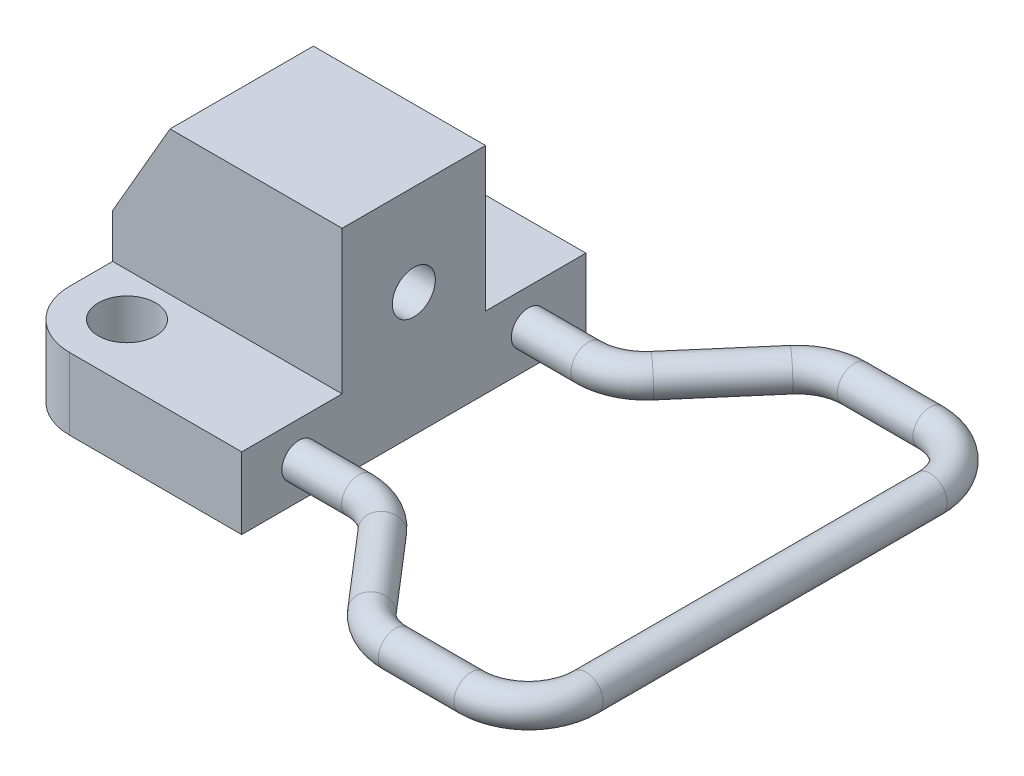
SolidWorks part; units mm, degrees
ref_plane "前视基准面" through (0, 0, 0) normal (0, 0, 1) x (1, 0, 0)
ref_plane "上视基准面" through (0, 0, 0) normal (0, 1, 0) x (1, 0, 0)
ref_plane "右视基准面" through (0, 0, 0) normal (1, 0, 0) x (0, 0, -1)
other "Configuration Table"
sketch "草图15" plane through (0, 0, 0) normal (1, 0, 0) x (0, 0, -1)
  line L0 (-60, 0) -> (-25, 0)
  line L1 (-25, 0) -> (-25, 50)
  line L2 (-25, 50) -> (25, 50)
  line L3 (25, 50) -> (25, 0)
  line L4 (25, 0) -> (60, 0)
  line L5 (60, 0) -> (60, -25)
  line L6 (60, -25) -> (-60, -25)
  line L7 (-60, -25) -> (-60, 0)
  line L8 (0, 58.9623) -> (0, -46.6981) construction
  dimension "D1" = 25
  dimension "D2" = 50
  dimension "D3" = 120
  dimension "D4" = 50
extrude "凸台-拉伸3" add sketch "草图15" along normal mid plane 80
fillet "圆角1" radius 20 2 edges at (-40, -12.5, -60) (-40, -12.5, 60)
sketch "草图17" plane through (0, 0, 0) normal (0, 1, 0) x (1, 0, 0)
  circle A0 centre (-20, 40) radius 10
  arc A1 (-20, 60) -> (-40, 40) centre (-20, 40) ccw construction
  point P2 (-20.8857, 43.4487)
  dimension "D2" = 20
  dimension "D1" = 0
extrude "切除-拉伸2" cut sketch "草图17" against normal through all
mirror "镜向1" about plane through (0, 0, 0) normal (0, 0, 1) of "切除-拉伸2"
chamfer "倒角1" distance 20 angle 60 1 edges at (-40, 50, 0)
sketch "草图19" plane through (0, 0, 0) normal (0, 0, 1) x (1, 0, 0)
  line L0 (-30, 32.6795) -> (-11.9086, 22.2344)
  line L1 (-20, 50) -> (-40, 15.359) construction
  line L2 (3.0914, 18.2152) -> (40, 18.2152)
  line L3 (40, 50) -> (40, 0) construction
  line L4 (40, 50) -> (-20, 50) construction
  arc A0 (-11.9086, 22.2344) -> (3.0914, 18.2152) centre (3.0914, 48.2152) ccw
  point P11 (-30, 32.6795)
  dimension "D1" = 30
  dimension "D2" = 31.7848
sweep "切除-扫描2" cut path "草图19" circular profile diameter 15 parameters "D3"=15
ref_plane "基准面2" through (0, -12.5, 0) normal (0, 1, 0) x (1, 0, 0)
sketch "草图26" plane through (0, -12.5, 0) normal (0, 1, 0) x (1, 0, 0)
  line L0 (0, 0) -> (142.0119, 0) construction
  line L1 (40, 40) -> (60.8279, 40)
  line L2 (40, 60) -> (40, 25) construction
  line L3 (75.9844, 46.9508) -> (98.4541, 73.0492)
  line L4 (113.6106, 80) -> (140, 80)
  line L5 (160, 60) -> (160, -60)
  line L6 (40, 25) -> (40, -25) construction
  line L7 (40, -40) -> (60.8279, -40)
  line L8 (113.6106, -80) -> (140, -80)
  line L9 (75.9844, -46.9508) -> (98.4541, -73.0492)
  arc A0 (140, -80) -> (160, -60) centre (140, -60) ccw
  arc A1 (60.8279, -40) -> (75.9844, -46.9508) centre (60.8279, -60) cw
  arc A2 (113.6106, -80) -> (98.4541, -73.0492) centre (113.6106, -60) cw
  arc A3 (140, 80) -> (160, 60) centre (140, 60) cw
  arc A4 (98.4541, 73.0492) -> (113.6106, 80) centre (113.6106, 60) cw
  arc A5 (60.8279, 40) -> (75.9844, 46.9508) centre (60.8279, 60) ccw
  point P7 (134.4148, 0)
  point P16 (160, 0)
  point P19 (160, -80)
  point P22 (70, -40)
  point P25 (104.4385, -80)
  point P28 (160, 80)
  point P31 (104.4385, 80)
  point P34 (70, 40)
  dimension "D6" = 20
  dimension "D1" = 49.273
  dimension "D2" = 30
  dimension "D3" = 160
  dimension "D4" = 80
  dimension "D5" = 120
sweep "扫描2" add path "草图26" circular profile diameter 12 parameters "D3"=12
